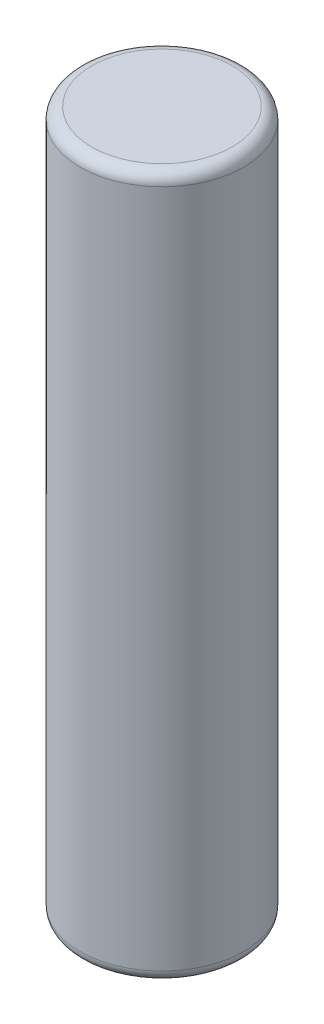
SolidWorks part; units mm, degrees
ref_plane "Front Plane" through (0, 0, 0) normal (0, 0, 1) x (1, 0, 0)
ref_plane "Top Plane" through (0, 0, 0) normal (0, 1, 0) x (1, 0, 0)
ref_plane "Right Plane" through (0, 0, 0) normal (1, 0, 0) x (0, 0, -1)
sketch "Sketch1" plane through (0, 0, 0) normal (0, 1, 0) x (1, 0, 0)
  circle A0 centre (0, 0) radius 7
  dimension "D1" = 14
extrude "Boss-Extrude1" add sketch "Sketch1" along normal blind 60
fillet "Fillet1" radius 1 2 edges at (0, 60, 7) (0, 0, 7)
